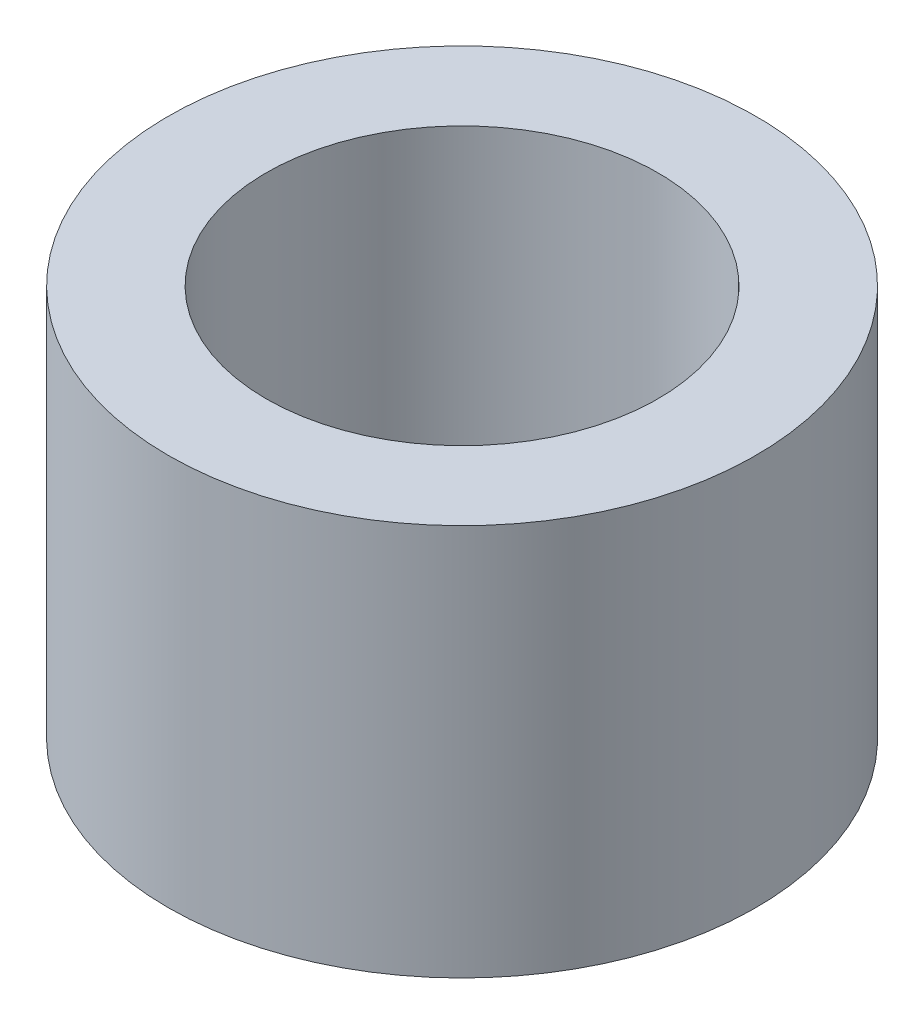
SolidWorks part; units mm, degrees
ref_plane "Front Plane" through (0, 0, 0) normal (0, 0, 1) x (1, 0, 0)
ref_plane "Top Plane" through (0, 0, 0) normal (0, 1, 0) x (1, 0, 0)
ref_plane "Right Plane" through (0, 0, 0) normal (1, 0, 0) x (0, 0, -1)
sketch "Sketch1" plane through (0, 0, 0) normal (0, 1, 0) x (1, 0, 0)
  circle A0 centre (0, 0) radius 7.5
  dimension "D1" = 15
extrude "Boss-Extrude1" add sketch "Sketch1" along normal blind 10
sketch "Sketch2" plane through (0, 10, 0) normal (0, 1, 0) x (1, 0, 0)
  circle A0 centre (0, 0) radius 5
  dimension "D1" = 10
extrude "Cut-Extrude1" cut sketch "Sketch2" against normal blind 10
